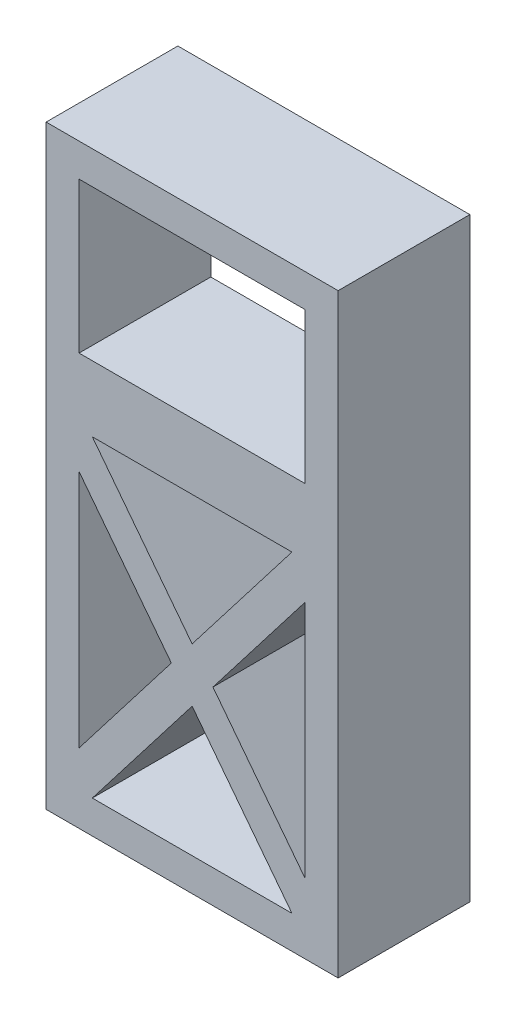
SolidWorks part; units mm, degrees
ref_plane "Front Plane" through (0, 0, 0) normal (0, 0, 1) x (1, 0, 0)
ref_plane "Top Plane" through (0, 0, 0) normal (0, 1, 0) x (1, 0, 0)
ref_plane "Right Plane" through (0, 0, 0) normal (1, 0, 0) x (0, 0, -1)
sketch "Sketch1" plane through (0, 0, 0) normal (0, 0, 1) x (1, 0, 0)
  line L0 (-28.15, -20.875) -> (28.15, -20.875) construction
  line L6 (-28.15, -20.875) -> (-28.15, 20.875)
  line L7 (-28.15, 20.875) -> (28.15, 20.875)
  line L8 (28.15, -20.875) -> (28.15, 20.875)
  line L9 (-28.15, 20.875) -> (28.15, -20.875) construction
  line L10 (-28.15, -20.875) -> (28.15, 20.875) construction
  line L11 (-21.8, 14.525) -> (21.8, 14.525)
  line L12 (-21.8, 14.525) -> (-21.8, -14.525)
  line L13 (-21.8, -14.525) -> (21.8, -14.525)
  line L14 (21.8, 14.525) -> (21.8, -14.525)
  line L15 (-21.8, 14.525) -> (21.8, -14.525) construction
  line L16 (-21.8, -14.525) -> (21.8, 14.525) construction
  line L17 (-28.15, -20.875) -> (-28.15, -93.9)
  line L18 (-28.15, -93.9) -> (28.15, -93.9)
  line L19 (28.15, -20.875) -> (28.15, -93.9)
  line L20 (-28.15, -20.875) -> (28.15, -93.9) construction
  line L21 (-28.15, -93.9) -> (28.15, -20.875) construction
  line L22 (-19.2453, -27.225) -> (0, -52.1875)
  line L23 (21.8, -34.3114) -> (4.009, -57.3875)
  line L24 (19.2453, -27.225) -> (0, -52.1875)
  line L26 (-4.009, -57.3875) -> (-21.8, -80.4636)
  line L27 (4.009, -57.3875) -> (21.8, -80.4636)
  line L28 (0, -62.5875) -> (-19.2453, -87.55)
  line L29 (0, -62.5875) -> (19.2453, -87.55)
  line L30 (-19.2453, -27.225) -> (19.2453, -27.225)
  line L31 (21.8, -34.3114) -> (21.8, -80.4636)
  line L32 (19.2453, -87.55) -> (-19.2453, -87.55)
  line L33 (-21.8, -80.4636) -> (-21.8, -34.3114)
  line L34 (-21.8, -34.3114) -> (-4.009, -57.3875)
  point P0 (0, 0)
  point P8 (0, 0)
  point P9 (0, 0)
  dimension "D8" = 6.35
  dimension "D1" = 6.35
  dimension "D2" = 29.05
  dimension "D3" = 6.35
  dimension "D4" = 43.6
  dimension "D5" = 79.375
  dimension "D6" = 3.175
  dimension "D7" = 3.175
  dimension "D10" = 6.35
  dimension "D12" = 3.175
  dimension "D13" = 3.175
  dimension "D14" = 3.175
extrude "Boss-Extrude1" add sketch "Sketch1" along normal blind 25.4
